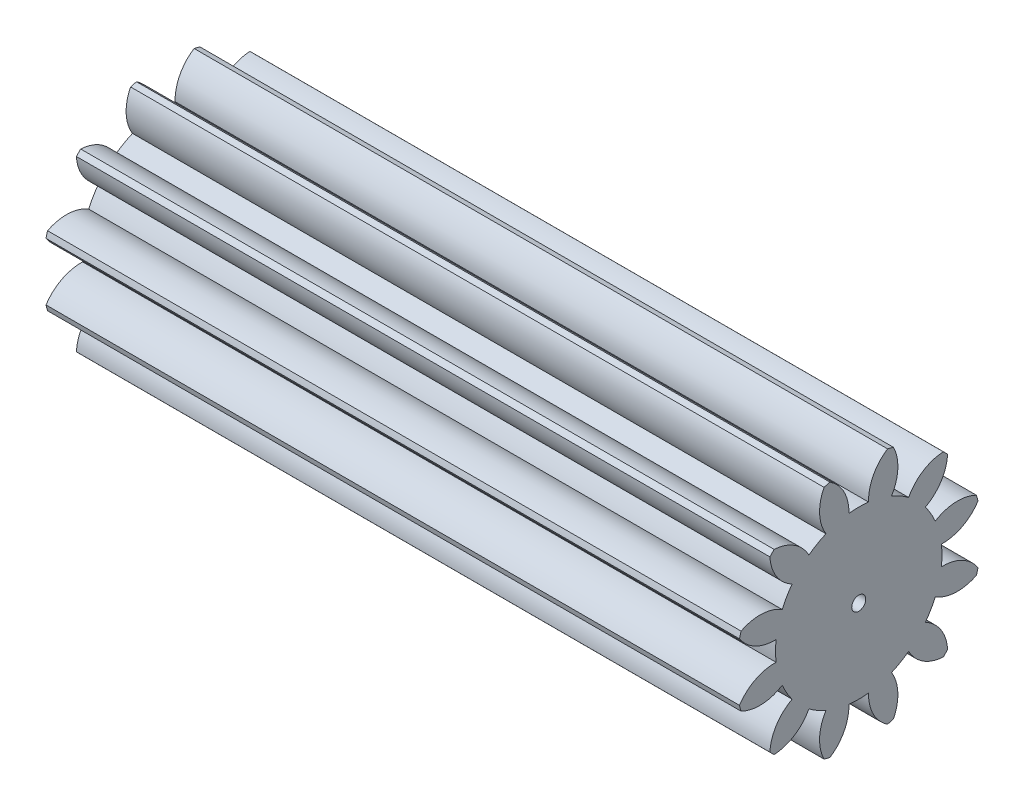
SolidWorks part; units mm, degrees
ref_plane "Plane1" through (0, 0, 0) normal (0, 0, 1) x (1, 0, 0)
ref_plane "Plane2" through (0, 0, 0) normal (0, 1, 0) x (1, 0, 0)
ref_plane "Plane3" through (0, 0, 0) normal (1, 0, 0) x (0, 0, -1)
sketch "HoldingSke" plane through (0, 0, 0) normal (0, 1, 0) x (1, 0, 0)
  line L0 (0, 0) -> (0.9781, -0.2079)
  line L1 (-15, 0) -> (100, 0) construction
  line L2 (0, 0) -> (-2.1039, 2.3779)
  line L3 (0, 0) -> (-11.863, 4.5341)
  line L4 (0, 0) -> (8.4473, 1.7955)
  line L5 (0, 0) -> (-46.8476, -17.4728)
  line L6 (0, 0) -> (-9.9476, -6.7116)
  line L7 (-2.1039, 2.3779) -> (8.6586, 51.2059)
  line L8 (-76.2, 54.61) -> (-76.1, 54.61)
  line L9 (-71.009, 38.7566) -> (-53.1078, 45.2721)
  line L10 (-76.2, 71.12) -> (104.1128, 71.12)
  line L11 (0, 0) -> (-12, 0)
  line L12 (-76.2, 101.6) -> (-76.162, 101.6)
  line L13 (24.9733, 27.94) -> (52.9518, 28.4284)
  line L14 (24.9733, 27.94) -> (24.9743, 27.94)
  line L15 (24.9733, 27.94) -> (100.4006, 29.5858)
  line L16 (-63.627, -1) -> (-12.827, -1)
  circle A0 centre (0, 0) radius 0.4
  circle A1 centre (0, 0) radius 4.749
  circle A2 centre (0, 0) radius 37.5
  circle A3 centre (0, 0) radius 0.4
  dimension "MHD" = 9.498
  dimension "Hub_dia" = 75
  dimension "Bore" = 0.8
  dimension "MBD" = 0.8
  dimension "Num_teeth" = 12
  dimension "Pitch" = 1
  dimension "Overall_len" = 50
  dimension "Show_teeth" = 12
  dimension "Thickness" = 12
  dimension "OAL" = 50.0001
  dimension "T_dim" = 0.1
  dimension "Ap" = 20
  dimension "H" = 19.05
  dimension "Pitch_radius" = 180.3128
  dimension "Width" = 12
  dimension "Backlash" = 0.038
  dimension "Addendum_fac" = 1
  dimension "Dedendum_fac" = 1.25
  dimension "Clearance_fac" = 0.25
  dimension "Dedendum_add" = 0.001
  dimension "Module" = 1
sketch "BasProSke" plane through (0, 0, 0) normal (0, 1, 0) x (1, 0, 0)
  line L0 (-10, 0) -> (60, 0) construction
  line L1 (0, 0) -> (0, 7)
  line L2 (0, 0) -> (39.565, 0)
  line L3 (39.565, 0) -> (39.565, 7)
  line L4 (39.565, 7) -> (0, 7)
  dimension "Thickness" = 39.565
  dimension "Diameter" = 14
revolve "Base-Revolve" add sketch "BasProSke" angle 360 about L0
sketch "TooCutSke" plane through (0, 0, 0) normal (1, 0, 0) x (0, 0, -1)
  line L1 (0, 0) -> (0, 107) construction
  line L2 (0, 0) -> (-0.8496, 5.9395) construction
  line L3 (0, 0) -> (-3.0836, 11.5081) construction
  line L4 (-0.8496, 5.9395) -> (-1.5418, 5.7541) construction
  arc A0 (0.5622, 4.7156) -> (-0.5622, 4.7156) centre (0, 0) ccw
  arc A1 (1.6729, 6.8233) -> (-1.6729, 6.8233) centre (0, 0) ccw
  circle A2 centre (0, 0) radius 6 construction
  circle A3 centre (0, 0) radius 5.6382 construction
  arc A4 (-0.5622, 4.7156) -> (-1.6729, 6.8233) centre (-2.9608, 4.7982) ccw
  arc A5 (1.6729, 6.8233) -> (0.5622, 4.7156) centre (2.9608, 4.7982) ccw
  dimension "Root_dia" = 9.498
  dimension "Overcut_dia" = 14.0508
  dimension "Pitch_dia" = 12
  dimension "Base_dia" = 11.2763
  dimension "Flank_rad" = 2.4
  dimension "Half_ang" = 15
  dimension "Half_CT" = 0.7167
extrude "ToothCut" cut sketch "TooCutSke" along normal through all
fillet "Breaks" [suppressed] radius 0.02
fillet "RootFillets" [suppressed] radius 0.251
pattern_circular "TeethCuts" count 12 every 30 about axis through (-10, 0, 0) along (1, 0, 0) of "ToothCut", "RootFillets", "Breaks"
sketch "HubNeaOneSke" plane through (0, 0, 0) normal (-1, 0, 0) x (0, 0, 1)
  circle A0 centre (0, 0) radius 4.749
  dimension "Diameter" = 9.498
extrude "HubNearOne" [suppressed] add sketch "HubNeaOneSke" along normal blind 10.4351
sketch "HubNeaBotSke" plane through (0, 0, 0) normal (-1, 0, 0) x (0, 0, 1)
  circle A0 centre (0, 0) radius 4.749
  dimension "Diameter" = 9.498
extrude "HubNearBoth" [suppressed] add sketch "HubNeaBotSke" along normal blind 5.2175
ref_plane "FarPln" through (39.565, 0, 0) normal (1, 0, 0) x (0, 0, -1)
sketch "HubFarSke" plane through (39.565, 0, 0) normal (1, 0, 0) x (0, 0, -1)
  circle A0 centre (0, 0) radius 4.749
  dimension "Diameter" = 9.498
extrude "HubFar" [suppressed] add sketch "HubFarSke" along normal blind 5.2175
sketch "BorSke" plane through (0, 0, 0) normal (1, 0, 0) x (0, 0, -1)
  circle A0 centre (0, 0) radius 0.4
  dimension "Diameter" = 0.8
extrude "Bore" cut sketch "BorSke" along normal mid plane 100.0001
sketch "KeySke" plane through (0, 0, 0) normal (1, 0, 0) x (0, 0, -1)
  line L0 (-0.05, 0) -> (-0.05, 0.5)
  line L1 (-0.05, 0.5) -> (0.05, 0.5)
  line L2 (0.05, 0.5) -> (0.05, 0)
  line L3 (0, 0) -> (0, 34) construction
  line L4 (-0.05, 0) -> (0.05, 0)
  dimension "Offset" = 0.5
  dimension "Width" = 0.1
extrude "Keyway" [suppressed] cut sketch "KeySke" along normal mid plane 100.0001
pattern_circular "Keyway2" [suppressed] count 2 every 90 about axis through (-10, 0, 0) along (1, 0, 0)
sketch "Sketch1" plane through (0, 0, 0) normal (-1, 0, 0) x (0, 0, 1)
  circle A0 centre (0, 0) radius 7
scale "Scale1" scale about centroid uniform scaling yes scale factor 2
sketch "Sketch5" plane through (-19.7825, 0, 0) normal (-1, 0, 0) x (0, 0, 1)
  circle A0 centre (0, 0) radius 4
extrude "Cut-Extrude2" cut sketch "Sketch5" against normal blind 5
sketch "Sketch6" plane through (59.3475, 0, 0) normal (1, 0, 0) x (0, 0, -1)
  circle A0 centre (0, 0) radius 11.811 construction
  dimension "D1" = 23.622
sketch "Sketch8" plane through (-14.7825, 0, 0) normal (-1, 0, 0) x (0, 0, 1)
  line L2 (-1.85, 0) -> (-1.85, 3.5465)
  line L3 (-1.85, 0) -> (-1.85, -3.5465)
  arc A1 (-1.85, -3.5465) -> (-1.85, 3.5465) centre (0, 0) ccw
  circle A2 centre (0, 0) radius 4 construction
extrude "Cut-Extrude4" cut sketch "Sketch8" against normal blind 15
equation "' \"Module@HoldingSke\" = 6.35"
equation "' \"Num_teeth@HoldingSke\" = 12"
equation "' \"Ap@HoldingSke\" =  20"
equation "' \"Ap@HoldingSke\" = 20"
equation "' \"Width@HoldingSke\" = 0.5 * 25.4"
equation "' \"Hub_dia@HoldingSke\"= 1 * 25.4"
equation "' \"Hub_dia@HoldingSke\" = 1 * 25.4"
equation "' \"Overall_len@HoldingSke\" = 1.0 * 25.4"
equation "' \"Bore@HoldingSke\" = 0.75 * 25.4"
equation "' \"T_dim@HoldingSke\" = 0.1 * 25.4"
equation "' \"Width@KeySke\" = 0.25 * 25.4"
equation "' \"Show_teeth@HoldingSke\" = 13"
equation "' \"Backlash@HoldingSke\" = 0.009 * 25.4"
equation "' \"Addendum_fac@HoldingSke\" = 1.0"
equation "' \"Dedendum_fac@HoldingSke\" = 1.25"
equation "' \"Dedendum_add@HoldingSke\" = 0.00005 * 25.4"
equation "' \"Clearance_fac@HoldingSke\" = 0.25"
equation "\"Pitch@HoldingSke\" = 1 / \"Module@HoldingSke\""
equation "\"Overcut_dia@TooCutSke\" = (\"Num_teeth@HoldingSke\" + 2 * \"Addendum_fac@HoldingSke\") / \"Pitch@HoldingSke\" + 0.002 * 25.4"
equation "\"Pitch_dia@TooCutSke\" = \"Num_teeth@HoldingSke\" / \"Pitch@HoldingSke\""
equation "\"Base_dia@TooCutSke\" = \"Num_teeth@HoldingSke\" / \"Pitch@HoldingSke\" * cos((\"Ap@HoldingSke\"  * 3.14159265 / 180))"
equation "\"Root_dia@TooCutSke\" = (\"Num_teeth@HoldingSke\" + 2) / \"Pitch@HoldingSke\" - 2 * (\"Addendum_fac@HoldingSke\" + \"Dedendum_fac@HoldingSke\") / \"Pitch@HoldingSke\" - \"Dedendum_add@HoldingSke\" * 2"
equation "\"Half_ang@TooCutSke\" = 180 / \"Num_teeth@HoldingSke\""
equation "\"Half_CT@TooCutSke\" = \"Num_teeth@HoldingSke\" / \"Pitch@HoldingSke\" * sin((3.14159265 / 2 / \"Num_teeth@HoldingSke\")) / 2 - 7 * \"Backlash@HoldingSke\" / 4"
equation "\"Flank_rad@TooCutSke\" = \"Num_teeth@HoldingSke\" / \"Pitch@HoldingSke\" / 5"
equation "\"Radius@RootFillets\" = \"Clearance_fac@HoldingSke\" / \"Pitch@HoldingSke\" + \"Dedendum_add@HoldingSke\""
equation "\"Break_rad@Breaks\" = 0.02 / \"Pitch@HoldingSke\""
equation "\"Thickness@HoldingSke\" = \"Width@HoldingSke\""
equation "\"OAL@HoldingSke\" = \"Thickness@HoldingSke\""
equation "\"MHD@HoldingSke\" = (\"Num_teeth@HoldingSke\" + 2) / \"Pitch@HoldingSke\" - 2 * (\"Addendum_fac@HoldingSke\" + \"Dedendum_fac@HoldingSke\")  / \"Pitch@HoldingSke\" - \"Dedendum_add@HoldingSke\" * 2"
equation "\"MBD@HoldingSke\" = (\"Num_teeth@HoldingSke\" + 2) / \"Pitch@HoldingSke\" - 2 * (\"Addendum_fac@HoldingSke\" + \"Dedendum_fac@HoldingSke\")  / \"Pitch@HoldingSke\" - \"Dedendum_add@HoldingSke\" * 2 - 0.002 * 25.4"
equation "\"MHD@HoldingSke\" = ((sgn( \"MHD@HoldingSke\" - \"Hub_dia@HoldingSke\" )-1)*( \"MHD@HoldingSke\" - \"Hub_dia@HoldingSke\" ))/-2+ \"Hub_dia@HoldingSke\""
equation "\"MBD@HoldingSke\" = ((sgn( \"MBD@HoldingSke\" - \"Bore@HoldingSke\" )-1)*( \"MBD@HoldingSke\" - \"Bore@HoldingSke\" ))/-2+ \"Bore@HoldingSke\""
equation "\"OAL@HoldingSke\" = ((sgn( \"OAL@HoldingSke\" - \"Overall_len@HoldingSke\" )+1)*( \"OAL@HoldingSke\" - \"Overall_len@HoldingSke\" ))/2 + \"Overall_len@HoldingSke\" + 0.000002 * 25.4"
equation "\"Num_teeth@TeethCuts\" = int( \"Show_teeth@HoldingSke\" ) + 1"
equation "\"Num_teeth@TeethCuts\" = ((sgn( \"Num_teeth@TeethCuts\" - \"Num_teeth@HoldingSke\" )-1)*( \"Num_teeth@TeethCuts\" - \"Num_teeth@HoldingSke\" ))/-2+ \"Num_teeth@HoldingSke\""
equation "\"Num_teeth@TeethCuts\" = ((sgn( \"Num_teeth@TeethCuts\" - 2.0)+1)*( \"Num_teeth@TeethCuts\" - 2.0))/2 +2.0"
equation "\"Angle@TeethCuts\" = 360.0 / \"Num_teeth@HoldingSke\""
equation "\"Diameter@BasProSke\" = (\"Num_teeth@HoldingSke\" + 2 * \"Addendum_fac@HoldingSke\") / \"Pitch@HoldingSke\""
equation "' \"Fillet_rad@BasProSke\" =  \"Thickness@HoldingSke\" * 0.05"
equation "' \"Fillet_rad@BasProSke\" = \"Thickness@HoldingSke\" * 0.05"
equation "\"MHD@HoldingSke\" = ((sgn( \"MHD@HoldingSke\" - \"Root_dia@TooCutSke\" )-1)*( \"MHD@HoldingSke\" - \"Root_dia@TooCutSke\" ))/-2+ \"Root_dia@TooCutSke\""
equation "\"Diameter@HubNeaOneSke\" = \"MHD@HoldingSke\""
equation "\"Length@HubNearOne\" = \"OAL@HoldingSke\" - \"Thickness@BasProSke\""
equation "\"Diameter@HubNeaBotSke\" = \"MHD@HoldingSke\""
equation "\"Length@HubNearBoth\" = ( \"OAL@HoldingSke\" - \"Thickness@BasProSke\" ) / 2.0"
equation "\"Thickness@FarPln\" = \"Thickness@BasProSke\""
equation "\"Diameter@HubFarSke\" = \"MHD@HoldingSke\""
equation "\"Length@HubFar\" = ( \"OAL@HoldingSke\" - \"Thickness@BasProSke\" ) / 2.0"
equation "\"Diameter@BorSke\" = \"MBD@HoldingSke\""
equation "\"D1@Bore\" = \"OAL@HoldingSke\" * 2.0"
equation "\"D1@Keyway\" = \"OAL@HoldingSke\" * 2.0"
equation "\"Offset@KeySke\" = \"T_dim@HoldingSke\" + \"MBD@HoldingSke\" / 2.0"
